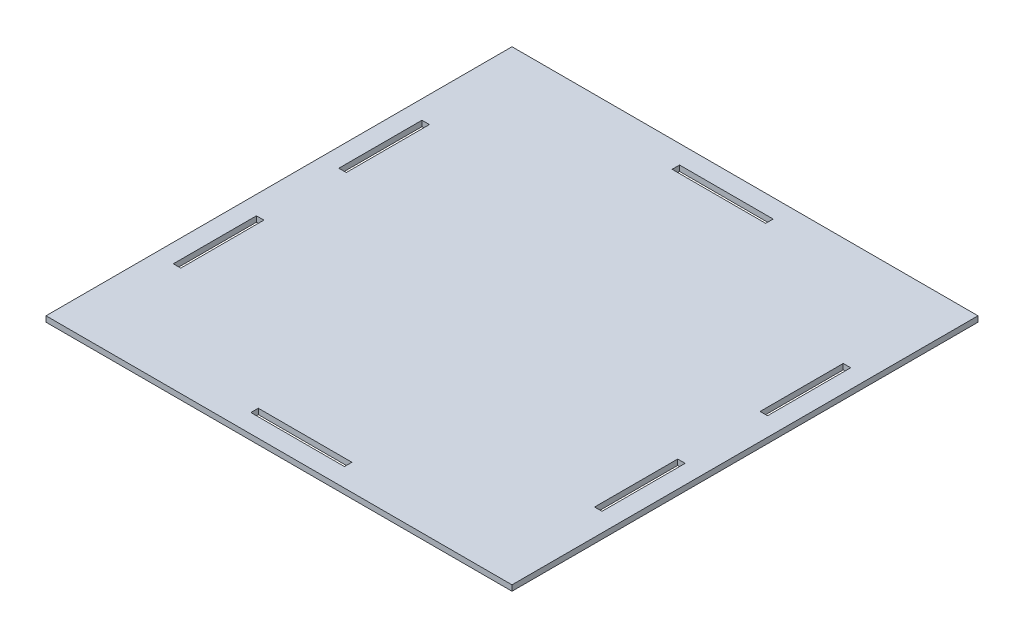
SolidWorks part; units mm, degrees
ref_plane "Front Plane" through (0, 0, 0) normal (0, 0, 1) x (1, 0, 0)
ref_plane "Top Plane" through (0, 0, 0) normal (0, 1, 0) x (1, 0, 0)
ref_plane "Right Plane" through (0, 0, 0) normal (1, 0, 0) x (0, 0, -1)
sketch "Sketch1" plane through (0, 0, 0) normal (0, 1, 0) x (1, 0, 0)
  line L1 (125, -125) -> (-125, -125)
  line L2 (125, -125) -> (125, 125)
  line L3 (125, 125) -> (-125, 125)
  line L4 (-125, -125) -> (-125, 125)
  line L5 (125, -125) -> (-125, 125) construction
  line L6 (125, 125) -> (-125, -125) construction
  line L11 (-25.1, 115) -> (25.1, 115)
  line L12 (-25.1, -111) -> (25.1, -111)
  line L16 (125, 0) -> (-125, 0) construction
  line L25 (0, 125) -> (0, -125) construction
  line L26 (111, -22.1) -> (115, -22.1)
  line L27 (111, -22.1) -> (111, -66.7)
  line L28 (111, -66.7) -> (115, -66.7)
  line L29 (115, -22.1) -> (115, -66.7)
  line L30 (111, -22.1) -> (115, -66.7) construction
  line L31 (111, -66.7) -> (115, -22.1) construction
  line L32 (-111, -66.7) -> (-115, -66.7)
  line L33 (-115, -22.1) -> (-115, -66.7)
  line L34 (-111, -22.1) -> (-115, -22.1)
  line L35 (-111, -22.1) -> (-111, -66.7)
  line L36 (111, 66.7) -> (115, 66.7)
  line L37 (115, 22.1) -> (115, 66.7)
  line L38 (111, 22.1) -> (115, 22.1)
  line L39 (111, 22.1) -> (111, 66.7)
  line L40 (-111, 22.1) -> (-111, 66.7)
  line L41 (-111, 22.1) -> (-115, 22.1)
  line L42 (-115, 22.1) -> (-115, 66.7)
  line L43 (-111, 66.7) -> (-115, 66.7)
  line L44 (-25.1, -111) -> (-25.1, -115)
  line L45 (-25.1, -115) -> (25.1, -115)
  line L46 (25.1, -111) -> (25.1, -115)
  line L47 (-25.1, -111) -> (25.1, -115) construction
  line L48 (-25.1, -115) -> (25.1, -111) construction
  line L49 (25.1, 111) -> (25.1, 115)
  line L50 (-25.1, 111) -> (25.1, 111)
  line L51 (-25.1, 111) -> (-25.1, 115)
  point P0 (0, 0)
  point P6 (0, -113)
  point P25 (113, -44.4)
  dimension "D1" = 250
  dimension "D2" = 250
  dimension "D3" = 50.2
  dimension "D4" = 4
  dimension "D5" = 10
  dimension "D6" = 80.6
  dimension "D8" = 4
  dimension "D9" = 44.6
  dimension "D12" = 10
extrude "Boss-Extrude2" add sketch "Sketch1" along normal blind 3
